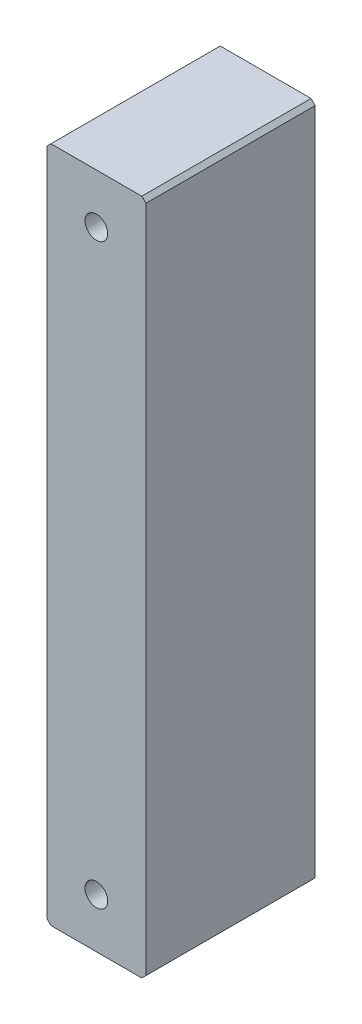
SolidWorks part; units mm, degrees
ref_plane "Front Plane" through (0, 0, 0) normal (0, 0, 1) x (1, 0, 0)
ref_plane "Top Plane" through (0, 0, 0) normal (0, 1, 0) x (1, 0, 0)
ref_plane "Right Plane" through (0, 0, 0) normal (1, 0, 0) x (0, 0, -1)
sketch "Croquis2" plane through (0, 0, 0) normal (0, 0, 1) x (1, 0, 0)
  line L0 (-592.2827, 986.4189) -> (-591.2827, 987.4189)
  line L1 (-591.2827, 823.4189) -> (-569.2827, 823.4189)
  line L2 (-592.2827, 824.4189) -> (-592.2827, 986.4189)
  line L3 (-591.2827, 987.4189) -> (-569.2827, 987.4189)
  line L4 (-568.2827, 824.4189) -> (-568.2827, 986.4189)
  line L5 (-592.2827, 823.4189) -> (-568.2827, 987.4189) construction
  line L6 (-592.2827, 987.4189) -> (-568.2827, 823.4189) construction
  line L7 (-569.2827, 987.4189) -> (-568.2827, 986.4189)
  line L8 (-591.2827, 823.4189) -> (-592.2827, 824.4189)
  line L9 (-569.2827, 823.4189) -> (-568.2827, 824.4189)
  line L10 (-580.2827, 978.1689) -> (-580.2827, 832.6689) construction
  circle A0 centre (-580.2827, 975.4189) radius 2.75
  circle A1 centre (-580.2827, 835.4189) radius 2.75
  point P0 (-580.2827, 905.4189)
  point P14 (-580.2827, 905.4189)
  dimension "D3" = 5.5
  dimension "D4" = 5.5
  dimension "D9" = 140
  dimension "D1" = 164
  dimension "D2" = 24
extrude "Saliente-Extruir1" add sketch "Croquis2" along normal blind 41
